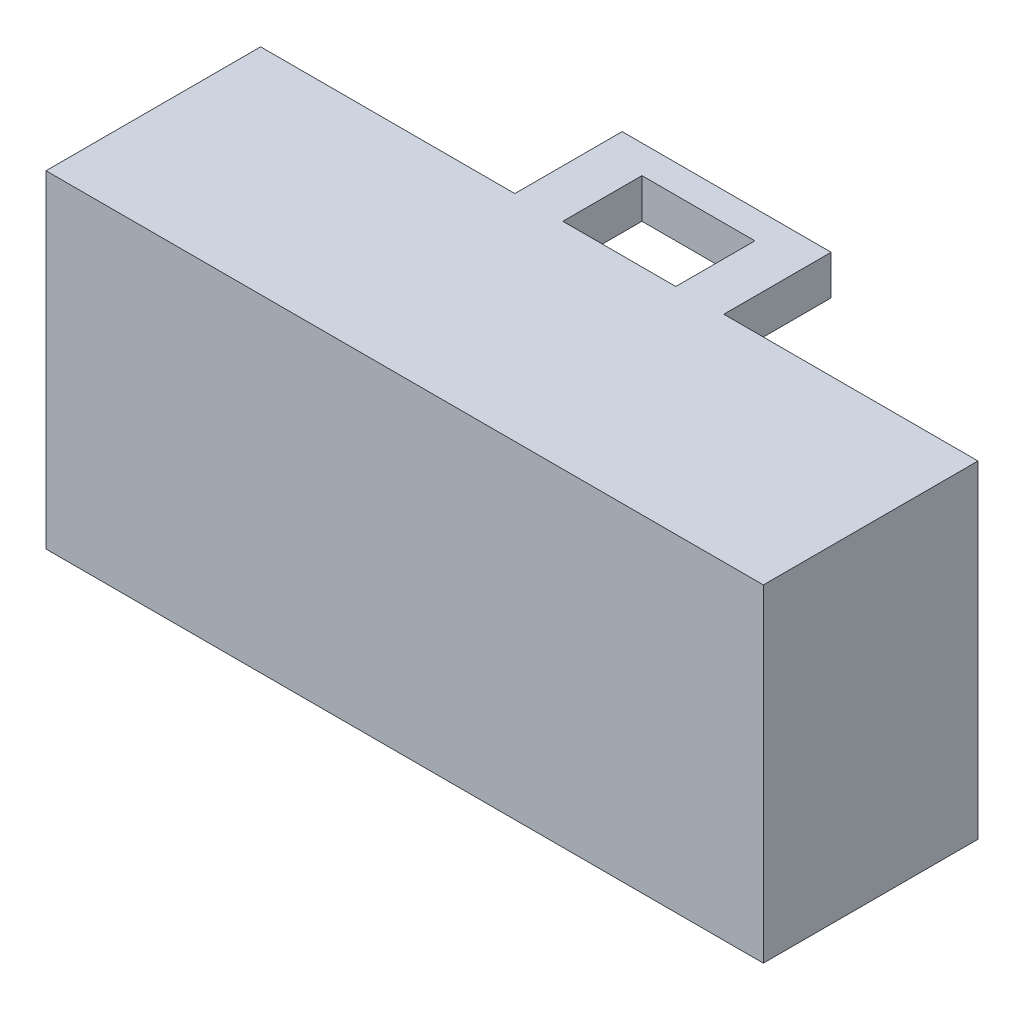
SolidWorks part; units mm, degrees
ref_plane "Alzado" through (0, 0, 0) normal (0, 0, 1) x (1, 0, 0)
ref_plane "Planta" through (0, 0, 0) normal (0, 1, 0) x (1, 0, 0)
ref_plane "Vista lateral" through (0, 0, 0) normal (1, 0, 0) x (0, 0, -1)
sketch "Croquis1" plane through (0, 0, 0) normal (0, 0, 1) x (1, 0, 0)
  line L1 (-6.35, -2.9) -> (6.35, -2.9)
  line L2 (-6.35, -2.9) -> (-6.35, 2.9)
  line L3 (-6.35, 2.9) -> (6.35, 2.9)
  line L4 (6.35, -2.9) -> (6.35, 2.9)
  line L5 (-6.35, -2.9) -> (6.35, 2.9) construction
  line L6 (-6.35, 2.9) -> (6.35, -2.9) construction
  point P0 (0, 0)
  dimension "D1" = 12.7
  dimension "D2" = 5.8
extrude "Saliente-Extruir1" add sketch "Croquis1" along normal blind 3.8
sketch "Croquis2" plane through (0, 0, 0) normal (0, 0, 1) x (1, 0, 0)
  line L0 (-6.35, -2.9) -> (6.35, -2.9) construction
  line L1 (1.85, 2.9) -> (-1.85, 2.9)
  line L2 (1.85, 2.9) -> (1.85, -2.9) construction
  line L3 (1.85, -2.9) -> (-1.85, -2.9)
  line L4 (-1.85, 2.9) -> (-1.85, -2.9) construction
  line L5 (1.85, 2.9) -> (-1.85, -2.9) construction
  line L6 (1.85, -2.9) -> (-1.85, 2.9) construction
  line L7 (-1.85, -2.9) -> (-1.85, -2.2)
  line L8 (-1.85, -2.2) -> (1.85, -2.2)
  line L9 (1.85, -2.2) -> (1.85, -2.9)
  line L10 (-1.85, 2.9) -> (-1.85, 2.2)
  line L11 (-1.85, 2.2) -> (1.85, 2.2)
  line L12 (1.85, 2.2) -> (1.85, 2.9)
  point P0 (0, 0)
  dimension "D1" = 3.7
  dimension "D2" = 0.7
  dimension "D3" = 0.7
extrude "Saliente-Extruir2" add sketch "Croquis2" against normal blind 1.9
sketch "Croquis3" plane through (0, 0, 0) normal (0, 1, 0) x (1, 0, 0)
  line L0 (0, 0) -> (0, 0.7) construction
  line L1 (-1.85, 0) -> (-1.5591, 0) construction
  line L3 (1, 1.4) -> (-1, 1.4)
  line L4 (1, 1.4) -> (1, 0)
  line L5 (1, 0) -> (-1, 0)
  line L6 (-1, 1.4) -> (-1, 0)
  line L7 (1, 1.4) -> (-1, 0) construction
  line L8 (1, 0) -> (-1, 1.4) construction
  dimension "D1" = 0.7
  dimension "D2" = 2
extrude "Cortar-Extruir1" cut sketch "Croquis3" against normal mid plane 5.9
